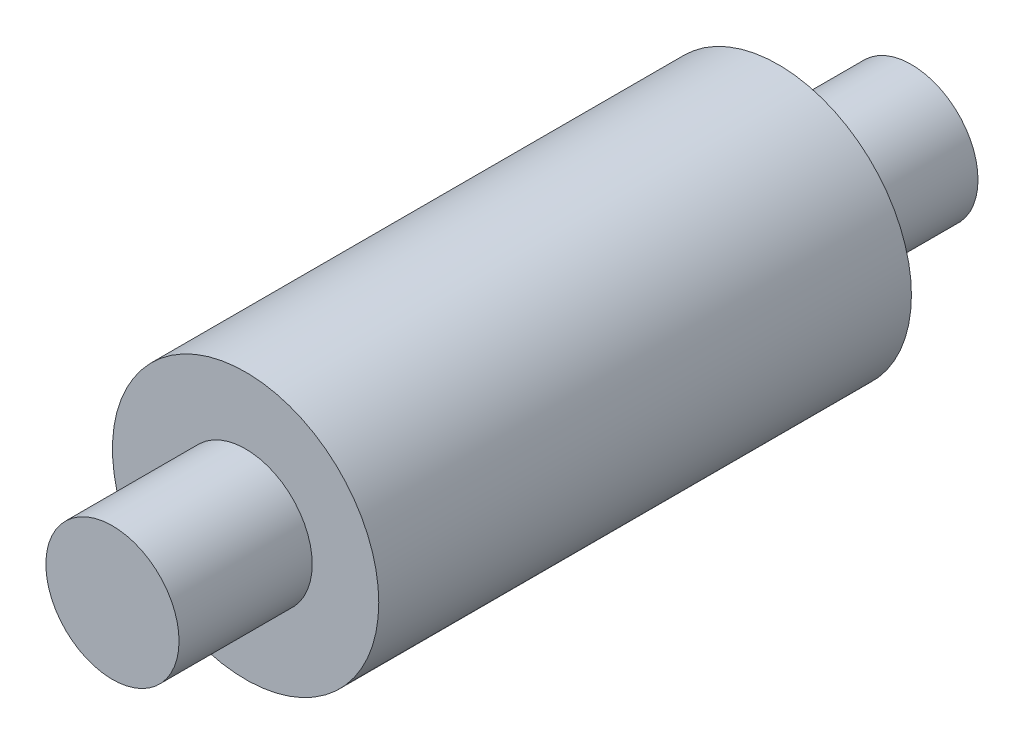
SolidWorks part; units mm, degrees
ref_plane "Front Plane" through (0, 0, 0) normal (0, 0, 1) x (1, 0, 0)
ref_plane "Top Plane" through (0, 0, 0) normal (0, 1, 0) x (1, 0, 0)
ref_plane "Right Plane" through (0, 0, 0) normal (1, 0, 0) x (0, 0, -1)
sketch "Sketch1" plane through (0, 0, 0) normal (0, 0, 1) x (1, 0, 0)
  circle A0 centre (0, 0) radius 5
  dimension "D1" = 10
extrude "Boss-Extrude1" add sketch "Sketch1" along normal mid plane 20
sketch "Sketch2" plane through (0, 0, 10) normal (0, 0, 1) x (1, 0, 0)
  circle A0 centre (0, 0) radius 2.5
  dimension "D1" = 5
extrude "Boss-Extrude2" add sketch "Sketch2" along normal blind 5
mirror "Mirror1" about plane through (0, 0, 0) normal (0, 0, 1) of "Boss-Extrude2"
